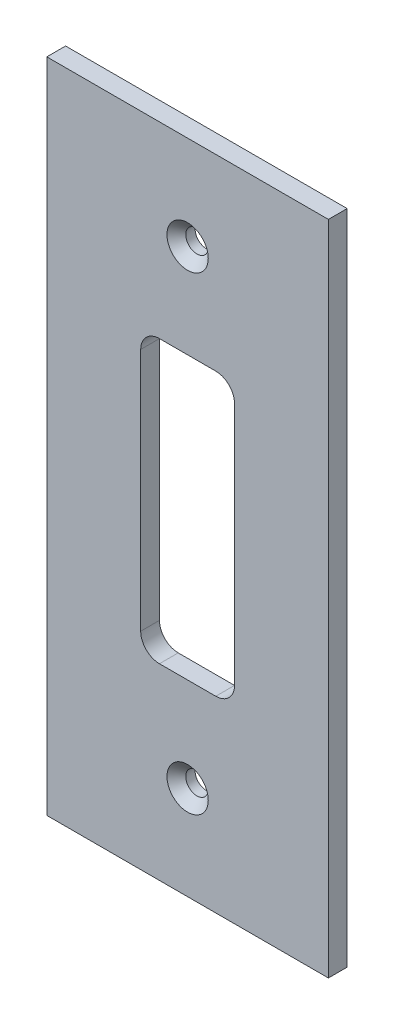
SolidWorks part; units mm, degrees
ref_plane "Front Plane" through (0, 0, 0) normal (0, 0, 1) x (1, 0, 0)
ref_plane "Top Plane" through (0, 0, 0) normal (0, 1, 0) x (1, 0, 0)
ref_plane "Right Plane" through (0, 0, 0) normal (1, 0, 0) x (0, 0, -1)
other "Configuration Table"
sketch "Sketch1" plane through (0, 0, 0) normal (0, 0, 1) x (1, 0, 0)
  line L1 (0, 0) -> (30, 0)
  line L2 (0, 0) -> (0, 70)
  line L3 (0, 70) -> (30, 70)
  line L4 (30, 0) -> (30, 70)
  line L5 (12, 50) -> (18, 50)
  line L6 (10, 48) -> (10, 22)
  line L7 (12, 20) -> (18, 20)
  line L8 (20, 48) -> (20, 22)
  arc A0 (12, 50) -> (10, 48) centre (12, 48) ccw
  arc A1 (18, 50) -> (20, 48) centre (18, 48) cw
  arc A2 (18, 20) -> (20, 22) centre (18, 22) ccw
  arc A3 (10, 22) -> (12, 20) centre (12, 22) ccw
  dimension "D1" = 2
  dimension "D2" = 10
  dimension "D3" = 20
  dimension "D4" = 20
  dimension "D5" = 50
  dimension "D6" = 30
  dimension "D7" = 70
extrude "Extrude1" add sketch "Sketch1" against normal blind 2
hole_wizard "CSK for  Flat Head Machine Screw1" positions "Sketch3" profile "Sketch2" countersink size "M2" standard "Ansi Metric" end condition through all
sketch "Sketch3" plane through (0, 0, 0) normal (0, 0, 1) x (1, 0, 0)
  line L2 (0, 70) -> (0, 0) construction
  line L3 (18, 50) -> (12, 50) construction
  point P0 (15, 60)
  point P10 (15, 10)
  dimension "D1" = 15
  dimension "D2" = 50
  dimension "D3" = 10
sketch "Sketch2" plane through (15, 60, 0) normal (1, 0, 0) x (0, -1, 0)
  line L0 (0, 0) -> (0, 2)
  line L1 (0, 2) -> (1.2, 2)
  line L2 (1.2, 2) -> (1.2, 1)
  line L3 (1.2, 1) -> (2.2, 0)
  line L5 (2.2, 0) -> (0, 0)
  line L6 (-1.2, 1) -> (-2.2, 0) construction
  line L11 (0, -6.35) -> (0, 107.95) construction
  dimension "Thru Hole Dia." = 2.4
  dimension "Thru Hole Depth" = 2
  dimension "Near C'Sink Dia." = 4.4
  dimension "Near C'Sink Angle" = 90
